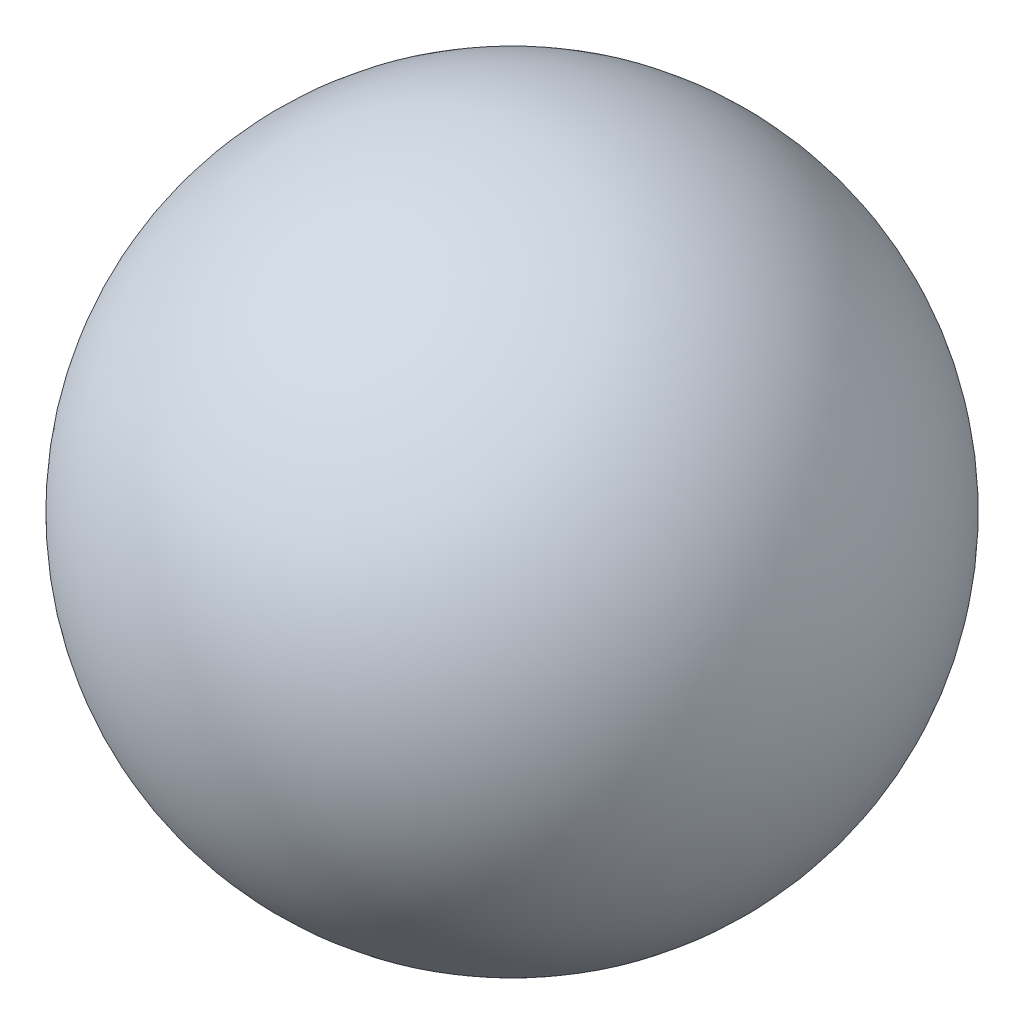
SolidWorks part; units mm, degrees
material "1060 Alloy"
ref_plane "Front Plane" through (0, 0, 0) normal (0, 0, 1) x (1, 0, 0)
ref_plane "Top Plane" through (0, 0, 0) normal (0, 1, 0) x (1, 0, 0)
ref_plane "Right Plane" through (0, 0, 0) normal (1, 0, 0) x (0, 0, -1)
sketch "Sketch1" plane through (0, 0, 0) normal (0, 0, 1) x (1, 0, 0)
  line L0 (0, 763.39) -> (0, 760)
  line L1 (0, -760) -> (0, -763.39)
  arc A0 (0, 760) -> (0, -760) centre (0, 0) ccw
  arc A1 (0, 763.39) -> (0, -763.39) centre (0, 0) ccw
revolve "Revolve1" add sketch "Sketch1" angle 360 about L1
